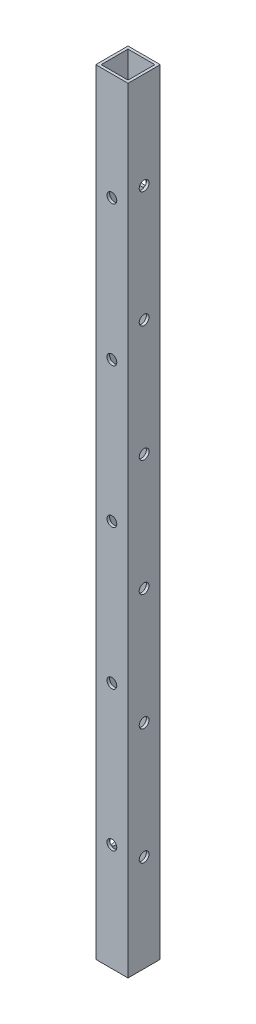
SolidWorks part; units mm, degrees
material "1060 Alloy"
ref_plane "Front Plane" through (0, 0, 0) normal (0, 0, 1) x (1, 0, 0)
ref_plane "Top Plane" through (0, 0, 0) normal (0, 1, 0) x (1, 0, 0)
ref_plane "Right Plane" through (0, 0, 0) normal (1, 0, 0) x (0, 0, -1)
sketch "Sketch1" plane through (0, 0, 0) normal (0, 1, 0) x (1, 0, 0)
  line L1 (-9.525, 9.525) -> (9.525, 9.525)
  line L2 (-9.525, 9.525) -> (-9.525, -9.525)
  line L3 (-9.525, -9.525) -> (9.525, -9.525)
  line L4 (9.525, 9.525) -> (9.525, -9.525)
  line L5 (-9.525, 9.525) -> (9.525, -9.525) construction
  line L6 (-9.525, -9.525) -> (9.525, 9.525) construction
  line L7 (-7.9375, 7.9375) -> (7.9375, 7.9375)
  line L8 (-7.9375, 7.9375) -> (-7.9375, -7.9375)
  line L9 (-7.9375, -7.9375) -> (7.9375, -7.9375)
  line L10 (7.9375, 7.9375) -> (7.9375, -7.9375)
  line L11 (-7.9375, 7.9375) -> (7.9375, -7.9375) construction
  line L12 (-7.9375, -7.9375) -> (7.9375, 7.9375) construction
  point P0 (0, 0)
  point P5 (0, 0)
  dimension "D1" = 19.05
  dimension "D2" = 19.05
  dimension "D3" = 15.875
extrude "Tube" add sketch "Sketch1" along normal blind 457.7532
sketch "Sketch2" plane through (0, 0, 9.525) normal (0, 0, 1) x (1, 0, 0)
  line L0 (0, 394.3548) -> (0, 457.7532) construction
  line L2 (-9.525, 457.7532) -> (9.525, 457.7532) construction
  line L7 (0, 63.3984) -> (0, 0) construction
  circle A2 centre (0, 394.3548) radius 2.8956
  dimension "D1" = 5.7912
  dimension "D2" = 63.3984
extrude "TopPlateHoles" cut sketch "Sketch2" against normal through all
pattern_linear "LPattern1" count 5 spacing 82.7391 along (0, -1, 0) of "TopPlateHoles"
sketch "Sketch3" plane through (-9.525, 0, 0) normal (-1, 0, 0) x (0, 0, 1)
  line L0 (0, 400.6032) -> (0, 457.7532) construction
  line L1 (-9.525, 457.7532) -> (9.525, 457.7532) construction
  circle A0 centre (0, 400.6032) radius 2.8956
  dimension "D1" = 5.7912
  dimension "D2" = 57.15
extrude "SidePlateHoleMaster" cut sketch "Sketch3" against normal through all
pattern_linear "LPattern2" count 6 spacing 68.6906 along (0, -1, 0) of "SidePlateHoleMaster"
equation "\"Height\"= 32in"
equation "\"Width\"= 23in"
equation "\"Depth\"= 20in"
equation "\"Plexi\"= .121in"
equation "\"Cutwidth\"= .016in"
equation "\"Earsize\"= 1in + \"Cutwidth\" /2"
equation "\"Slotsize\" = 1in - \"CutWidth\" / 2"
equation "\"InnerWidth\" = \"Width\" - 2* \"Plexi\""
equation "\"InnerHeight\" = \"Height\" -2 * \"Plexi\""
equation "\"InnerDepth\" = \"Depth\" - 2*\"Plexi\""
equation "\"RearHoleSpacing\" = (\"Width\" - 2*\"RearHolesBorder\") / (\"RearNumHoles\"-1)"
equation "\"RivetDia\" = .228in"
equation "\"SlotDepth\" = \"Plexi\" + 0.75in + .005in"
equation "\"SideHoleSpacing\"= (\"Height\"-2*(1.75-\"Plexi\"))/5in"
equation "\"SideSlotWidth\"   = \"Plexi\"+.005in"
equation "\"SidePanelVertSpacing\" = (\"Height\"-2*(1.75-\"Plexi\")) / 5"
equation "\"BottomPanelSideHoleSpacing\" = (\"InnerDepth\"-2*(1.75-\"Plexi\")) / 4"
equation "\"Boxsize\" = .75in"
equation "\"Boxinner\" = .625in"
equation "\"CornerCube\" = 0.75in"
equation "\"RearNumHoles\" = 7"
equation "\"RearHolesBorder\" = 2.2"
equation "\"RearBarLength\" = (\"InnerWidth\"-2*\"CornerCube\")"
equation "\"RearTopNumHoles\" = 6"
equation "\"RearTopHolesBorder\" = 2.5"
equation "\"RearTopHolesSpacing\" = (\"Width\" - 2*\"RearTopHolesBorder\") / (\"RearTopNumHoles\"-1)"
equation "\"SideVertNumHoles\" = 6"
equation "\"SideVertHolesBorder\" = \"CornerCube\"+\"FingerLength\"+.9"
equation "\"SideVertHoleSpacing\" = (\"InnerHeight\" - 2*\"SideVertHolesBorder\") / (\"SideVertNumHoles\"-1)"
equation "\"FrontDoorGap\" = .1in"
equation "\"TopDepth\" = \"Depth\"-\"DoorPlexi\"-\"FrontDoorGap\""
equation "\"MagnetThickness\"=3mm"
equation "\"MagnetDiameter\"=12mm"
equation "\"DoorPlexi\" = \"Plexi\""
equation "\"TopBarDepth\" = \"Depth\"-\"DoorPlexi\"-\"Plexi\"-2*\"MagnetThickness\"-2*\"CornerCube\""
equation "\"D1@Tube\"=\"TopBarDepth\""
equation "\"D1@Sketch2\"=\"RivetDia\""
equation "\"SideTopNumHoles\" = 5"
equation "\"SideTopHoleOffset\"=\"CornerCube\"+\"FingerLength\"+\"Plexi\"+.5"
equation "\"SideTopHoleSpacing\" = (\"TopBarDepth\"-2*\"SideTopHoleOffset\") / (\"SideTopNumHoles\"-1)"
equation "\"D2@Sketch2\"=\"SideTopHoleOffset\""
equation "\"FingerLength\" = 1.125in"
equation "\"D3@LPattern1\"=\"SideTopHoleSpacing\""
equation "\"D1@LPattern1\"=\"SideTopNumHoles\""
equation "\"D1@Sketch3\"=\"RivetDia\""
equation "\"SideHorizNumHoles\" = 6"
equation "\"SideHorizHoleBorder\" = 2.25"
equation "\"SideHorizHoleSpacing\" = (\"TopBarDepth\"-2*\"SideHorizHoleBorder\") / (\"SideHorizNumHoles\"-1)"
equation "\"D2@Sketch3\"=\"SideHorizHoleBorder\""
equation "\"D3@LPattern2\"=\"SideHorizHoleSpacing\""
equation "\"D1@LPattern2\"=\"SideHorizNumHoles\""
equation "\"D3@Sketch1\"=\"Boxinner\""
